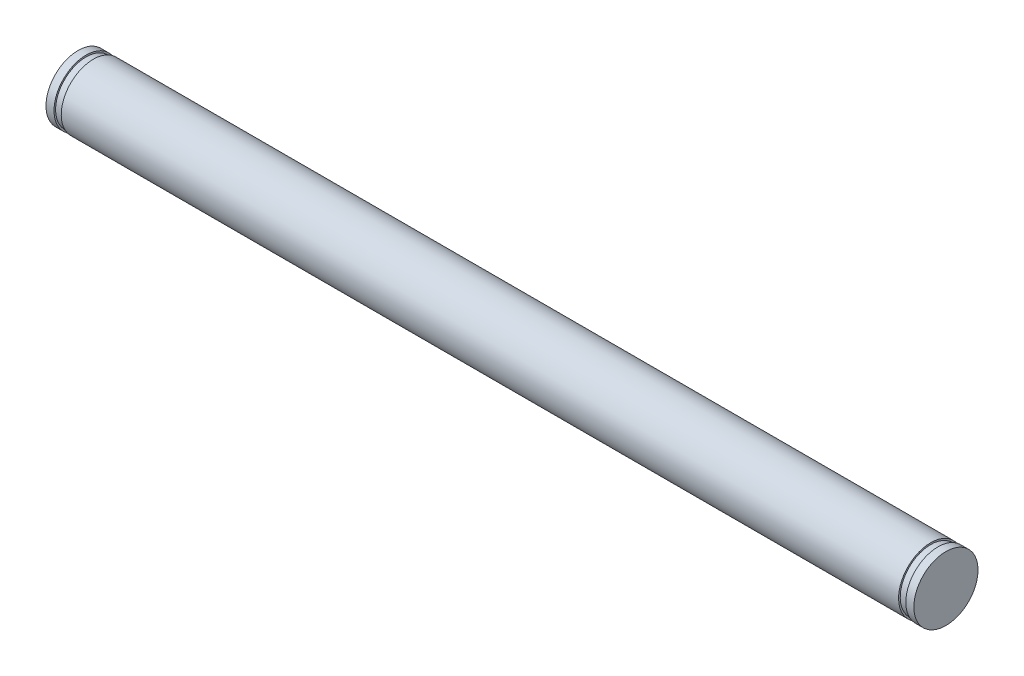
SolidWorks part; units mm, degrees
material "Plain Carbon Steel"
ref_plane "Front Plane" through (0, 0, 0) normal (0, 0, 1) x (1, 0, 0)
ref_plane "Top Plane" through (0, 0, 0) normal (0, 1, 0) x (1, 0, 0)
ref_plane "Right Plane" through (0, 0, 0) normal (1, 0, 0) x (0, 0, -1)
sketch "Sketch1" plane through (0, 0, 0) normal (0, 0, 1) x (1, 0, 0)
  line L0 (0, 0) -> (104.4, 0)
  line L1 (104.4, 0) -> (104.4, -0.2)
  line L2 (104.4, -0.2) -> (105.3, -0.2)
  line L3 (105.3, -0.2) -> (105.3, 0)
  line L4 (105.3, 0) -> (106.3, 0)
  line L5 (106.3, 0) -> (106.3, -4)
  line L6 (106.3, -4) -> (10.4, -4)
  line L7 (0, -0.2) -> (0, 0)
  line L8 (52.2, 0) -> (52.2, -4) construction
  line L9 (-1.9, 0) -> (-1.9, -4)
  line L10 (-0.9, 0) -> (-1.9, 0)
  line L11 (-0.9, -0.2) -> (-0.9, 0)
  line L12 (0, -0.2) -> (-0.9, -0.2)
  line L13 (-1.9, -4) -> (10.4, -4)
  dimension "D1" = 104.4
  dimension "D2" = 0.9
  dimension "D3" = 4
  dimension "D4" = 3.8
  dimension "D5" = 1
revolve "Revolve1" add sketch "Sketch1" angle 360 about L6
